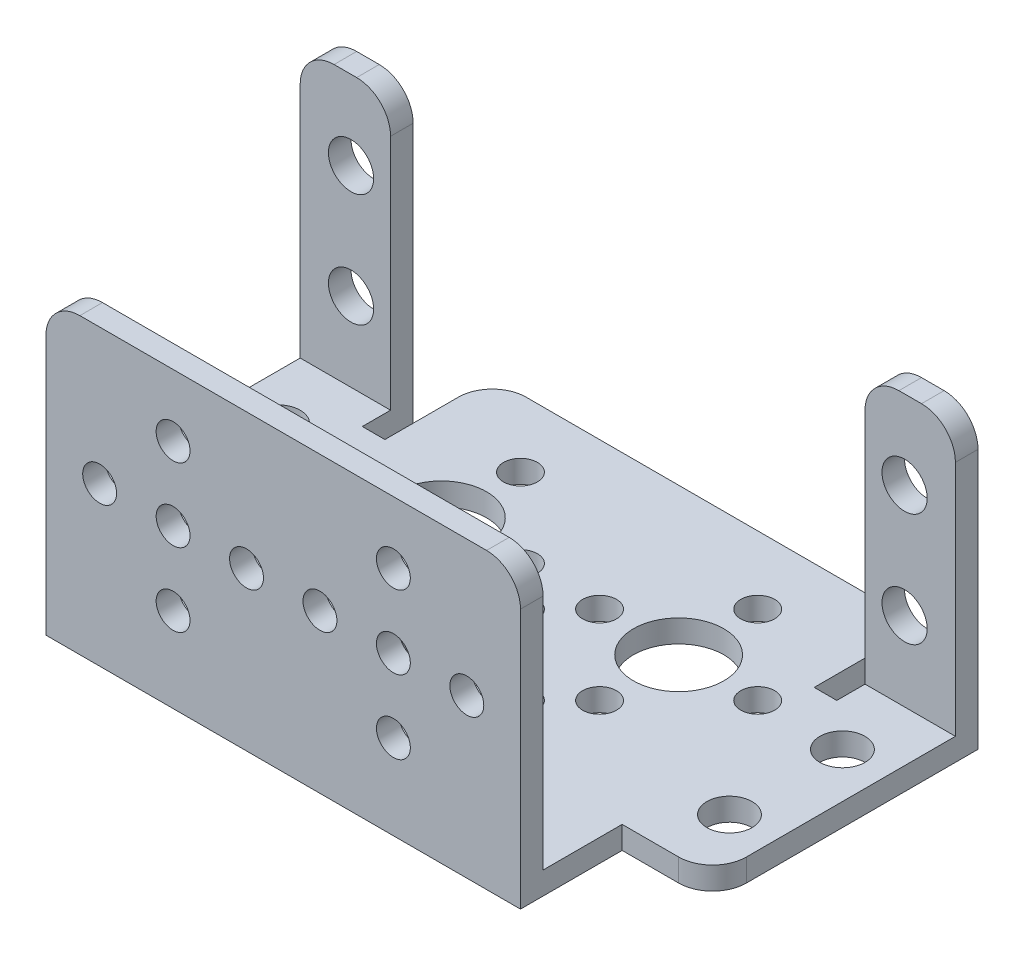
SolidWorks part; units mm, degrees
ref_plane "前视基准面" through (0, 0, 0) normal (0, 0, 1) x (1, 0, 0)
ref_plane "上视基准面" through (0, 0, 0) normal (0, 1, 0) x (1, 0, 0)
ref_plane "右视基准面" through (0, 0, 0) normal (1, 0, 0) x (0, 0, -1)
other "Configuration Table"
sketch "草图1" plane through (0, 0, 0) normal (0, 1, 0) x (1, 0, 0)
  line L0 (-29, 7) -> (-21, 7)
  line L1 (-21, 7) -> (-21, 0)
  line L2 (-21, 0) -> (21, 0)
  line L3 (0, 0) -> (0, 35.5) construction
  line L4 (19, 35.5) -> (-19, 35.5)
  line L5 (-29, 28.5) -> (-29, 7)
  line L6 (-21, 28.5) -> (-21, 26)
  line L7 (-21, 26) -> (-19, 26)
  line L8 (-19, 26) -> (-19, 35.5)
  line L9 (-21, 28.5) -> (-29, 28.5)
  line L10 (21, 28.5) -> (29, 28.5)
  line L11 (19, 26) -> (19, 35.5)
  line L12 (21, 26) -> (19, 26)
  line L13 (21, 28.5) -> (21, 26)
  line L14 (29, 28.5) -> (29, 7)
  line L15 (21, 7) -> (21, 0)
  line L16 (29, 7) -> (21, 7)
  line L17 (-25, 22.5) -> (-25, 28.5) construction
  circle A0 centre (-25, 12.5) radius 2
  circle A1 centre (-25, 22.5) radius 2
  circle A2 centre (25, 22.5) radius 2
  circle A3 centre (25, 12.5) radius 2
  circle A4 centre (-10.5, 22.5) radius 4
  circle A5 centre (-10.5, 29.5) radius 1.5
  circle A6 centre (-3.5, 22.5) radius 1.5
  circle A7 centre (-10.5, 15.5) radius 1.5
  circle A8 centre (-17.5, 22.5) radius 1.5
  circle A9 centre (3.5, 22.5) radius 1.5
  circle A10 centre (10.5, 15.5) radius 1.5
  circle A11 centre (17.5, 22.5) radius 1.5
  circle A12 centre (10.5, 22.5) radius 4
  circle A13 centre (10.5, 29.5) radius 1.5
  circle A14 centre (0, 12) radius 4
  circle A15 centre (0, 19) radius 1.5
  circle A16 centre (7, 12) radius 1.5
  circle A17 centre (0, 5) radius 1.5
  circle A18 centre (-7, 12) radius 1.5
  point P17 (-11.1534, 26)
  point P32 (-12.0284, 22.902)
  point P33 (-10.8012, 24.5384)
  point P41 (-10.5, 22.5)
  point P42 (-12.1381, 20.4752)
  point P43 (-10.2345, 23.9795)
  point P64 (0, 0)
  point P65 (0, 0)
  point P66 (0, 0)
  point P67 (0, 0)
  point P68 (0, 0)
  dimension "D3" = 4
  dimension "D4" = 12.5
  dimension "D5" = 4
  dimension "D6" = 10
  dimension "D14" = 8
  dimension "D15" = 3
  dimension "D16" = 21
  dimension "D17" = 7
  dimension "D18" = 8
  dimension "D19" = 3
  dimension "D20" = 3
  dimension "D21" = 3
  dimension "D22" = 3
  dimension "D23" = 12
  dimension "D25" = 7
  dimension "D1" = 28.5
  dimension "D2" = 35.5
  dimension "D7" = 38
  dimension "D8" = 58
  dimension "D9" = 2
  dimension "D10" = 26
  dimension "D11" = 7
  dimension "D13" = 7
  dimension "D24" = 7
  dimension "D26" = 7
  dimension "D27" = 10
  dimension "D12" = 4
extrude "凸台-拉伸1" add sketch "草图1" along normal blind 2
sketch "草图2" plane through (0, 0, 0) normal (0, -1, 0) x (1, 0, 0)
  line L0 (-21, -7) -> (-21, 0) construction
  line L1 (-29, -30.5) -> (-21, -30.5)
  line L2 (-29, -30.5) -> (-29, -28.5)
  line L3 (-29, -28.5) -> (-21, -28.5)
  line L4 (-21, -30.5) -> (-21, -28.5)
  line L6 (-21, 2) -> (21, 2)
  line L7 (-21, 2) -> (-21, 0)
  line L8 (-21, 0) -> (21, 0)
  line L9 (21, 2) -> (21, 0)
  line L10 (0, -1.1) -> (0, 1.1) construction
  line L11 (29, -28.5) -> (21, -28.5)
  line L12 (29, -30.5) -> (29, -28.5)
  line L13 (29, -30.5) -> (21, -30.5)
  line L14 (-21, -28.5) -> (-29, -28.5) construction
  line L15 (-29, -28.5) -> (-29, -7) construction
  line L16 (-21, 0) -> (21, 0) construction
  line L17 (21, -28.5) -> (21, -30.5)
  line M10 (-29, -28.5) -> (-21, -28.5)
  line M18 (21, -28.5) -> (29, -28.5)
  line M22 (21, 0) -> (-21, 0)
  dimension "D1" = 2
  dimension "D2" = 2
extrude "凸台-拉伸2" add sketch "草图2" against normal blind 26 contours L9 L6 L7 M22 | L1 L4 L2 M10 | L17 L13 L12 M18
sketch "草图3" plane through (0, 0, -30.5) normal (0, 0, 1) x (1, 0, 0)
  line L0 (-29, 26) -> (-21, 26) construction
  line L1 (-29, 26) -> (-29, 2) construction
  line L2 (0, -14.3) -> (0, 14.3) construction
  line L3 (-16.25, 14) -> (-21, 14) construction
  line L5 (16.25, 14) -> (21, 14) construction
  line L8 (21, 26) -> (21, 2) construction
  circle A0 centre (-24.5, 19) radius 2
  circle A1 centre (-24.5, 9) radius 2
  circle A2 centre (24.5, 9) radius 2
  circle A3 centre (24.5, 19) radius 2
  circle A4 centre (-16.25, 14) radius 1.5
  circle A5 centre (-9.75, 14) radius 1.5
  circle A6 centre (-3.25, 14) radius 1.5
  circle A7 centre (3.25, 14) radius 1.5
  circle A8 centre (9.75, 14) radius 1.5
  circle A9 centre (16.25, 14) radius 1.5
  circle A10 centre (-9.75, 7.5) radius 1.5
  circle A11 centre (-9.75, 20.5) radius 1.5
  circle A12 centre (9.75, 7.5) radius 1.5
  circle A13 centre (9.75, 20.5) radius 1.5
  point P30 (9.8558, 20.6148)
  point P32 (21, 14)
  point P40 (0, 0)
  point P41 (0, 0)
  dimension "D1" = 4
  dimension "D2" = 4
  dimension "D6" = 3
  dimension "D8" = 3
  dimension "D9" = 3
  dimension "D10" = 6.5
  dimension "D11" = 6.5
  dimension "D12" = 6.5
  dimension "D3" = 7
  dimension "D4" = 4.5
  dimension "D5" = 10
  dimension "D7" = 6
extrude "切除-拉伸1" cut sketch "草图3" along normal through all
fillet "圆角1" radius 3 10 edges at (21, 26, 1) (-21, 26, 1) (-19, 1, -35.5) (19, 1, -35.5) (-21, 26, -29.5) (-29, 26, -29.5) (21, 26, -29.5) (29, 26, -29.5) (29, 1, -7) (-29, 1, -7)
